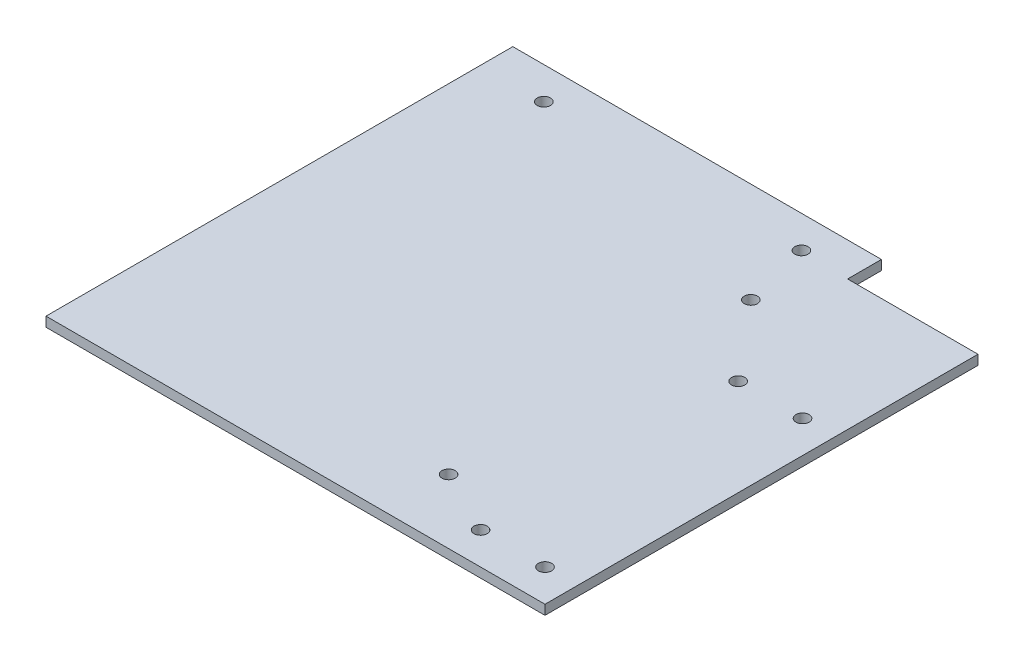
SolidWorks part; units mm, degrees
ref_plane "Front Plane" through (0, 0, 0) normal (0, 0, 1) x (1, 0, 0)
ref_plane "Top Plane" through (0, 0, 0) normal (0, 1, 0) x (1, 0, 0)
ref_plane "Right Plane" through (0, 0, 0) normal (1, 0, 0) x (0, 0, -1)
sketch "Sketch2" plane through (0, 0, 0) normal (0, 1, 0) x (1, 0, 0)
  line L1 (77.5, 72.5) -> (-77.5, 72.5)
  line L2 (77.5, 72.5) -> (77.5, -72.5)
  line L3 (77.5, -72.5) -> (-77.5, -72.5)
  line L4 (-77.5, 72.5) -> (-77.5, -72.5)
  line L5 (77.5, 72.5) -> (-77.5, -72.5) construction
  line L6 (77.5, -72.5) -> (-77.5, 72.5) construction
  point P0 (0, 0)
  dimension "D1" = 145
  dimension "D2" = 155
extrude "Boss-Extrude1" add sketch "Sketch2" along normal blind 3
sketch "Sketch3" plane through (0, 3, 0) normal (0, 1, 0) x (1, 0, 0)
  line L0 (0, 72.5) -> (0, 0)
  line L1 (77.5, 72.5) -> (-77.5, 72.5) construction
sketch "Sketch4" plane through (0, 3, 0) normal (0, 1, 0) x (1, 0, 0)
  line L1 (37, 72.5) -> (77.5, 72.5)
  line L2 (37, 72.5) -> (37, 62)
  line L3 (37, 62) -> (77.5, 62)
  line L4 (77.5, 72.5) -> (77.5, 62)
  line L5 (37, 72.5) -> (77.5, 62) construction
  line L6 (37, 62) -> (77.5, 72.5) construction
  line L7 (77.5, -72.5) -> (77.5, 72.5) construction
  point P4 (57.25, 67.25)
  dimension "D1" = 10.5
  dimension "D2" = 40.5
extrude "Cut-Extrude1" cut sketch "Sketch4" against normal blind 3
sketch "Sketch5" plane through (0, 3, 0) normal (0, 1, 0) x (1, 0, 0)
  line L0 (-57.85, 82.5) -> (-57.85, 62.5)
  line L1 (-57.85, 62.5) -> (22.15, 62.5) construction
  line L2 (-222.5, 17.5) -> (47.5, 17.5)
  line L3 (47.5, 17.5) -> (67.5, 17.5) construction
  line L4 (47.5, 17.5) -> (47.5, -62.5) construction
  circle A0 centre (-57.85, 62.5) radius 2.05
  circle A1 centre (22.15, 62.5) radius 2.05
  circle A2 centre (47.5, 17.5) radius 2.05
  circle A3 centre (67.5, 17.5) radius 2.05
  circle A4 centre (47.5, -62.5) radius 2.05
  circle A5 centre (67.5, -62.5) radius 2.05
  dimension "D1" = 4.1
  dimension "D5" = 270
  dimension "D6" = 4.1
  dimension "D2" = 20
  dimension "D4" = 80
  dimension "D8" = 20
  dimension "D10" = 80
  dimension "D3" = 2
  dimension "D7" = 2
  dimension "D9" = 2
extrude "Cut-Extrude2" cut sketch "Sketch5" against normal blind 3 contours A3 | A2 | A5 | A4 | A1 | A0
sketch "Sketch6" plane through (0, 3, 0) normal (0, 1, 0) x (1, 0, 0)
  circle A0 centre (27.5996, -52.5457) radius 2.05
  circle A1 centre (27.5996, 41.3418) radius 2.05
  dimension "D1" = 4.1
  dimension "D2" = 4.1
extrude "Cut-Extrude3" cut sketch "Sketch6" against normal blind 3
